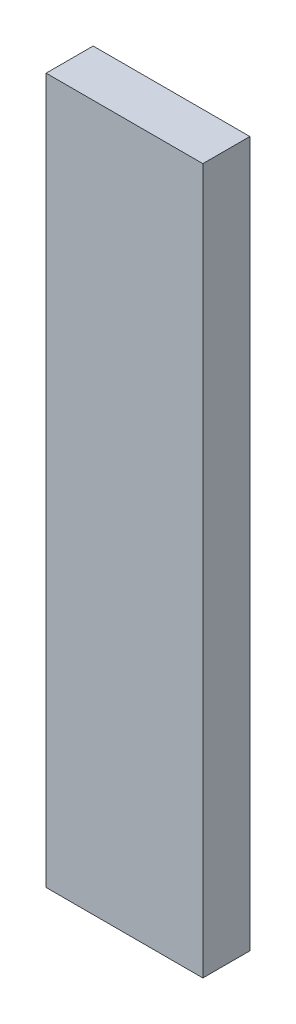
SolidWorks part; units mm, degrees
ref_plane "Front Plane" through (0, 0, 0) normal (0, 0, 1) x (1, 0, 0)
ref_plane "Top Plane" through (0, 0, 0) normal (0, 1, 0) x (1, 0, 0)
ref_plane "Right Plane" through (0, 0, 0) normal (1, 0, 0) x (0, 0, -1)
sketch "Sketch2" plane through (0, 0, 0) normal (0, 0, 1) x (1, 0, 0)
  line L1 (0, 0) -> (100, 0)
  line L2 (0, 0) -> (0, 450)
  line L3 (0, 450) -> (100, 450)
  line L4 (100, 0) -> (100, 450)
  dimension "D1" = 450
  dimension "D2" = 100
extrude "Boss-Extrude1" add sketch "Sketch2" along normal blind 30
